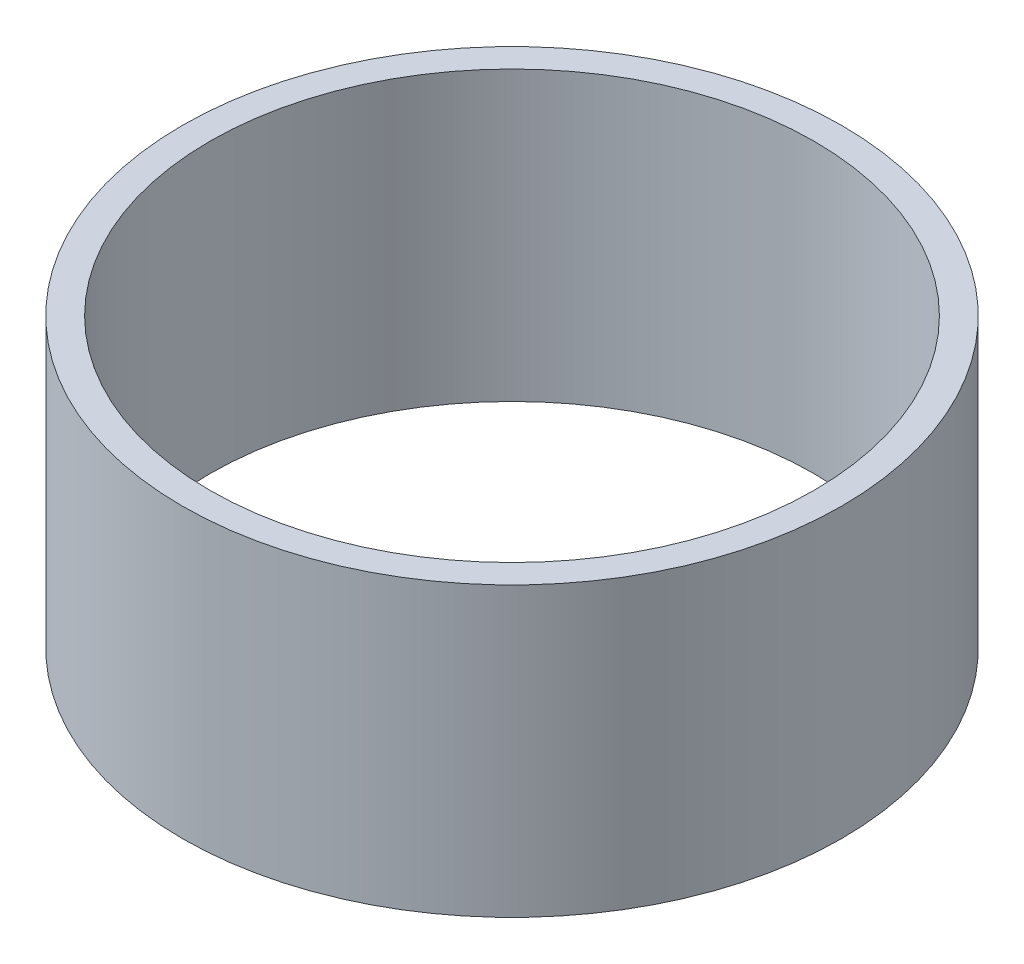
SolidWorks part; units mm, degrees
material "6061-T6 (SS)"
ref_plane "Front Plane" through (0, 0, 0) normal (0, 0, 1) x (1, 0, 0)
ref_plane "Top Plane" through (0, 0, 0) normal (0, 1, 0) x (1, 0, 0)
ref_plane "Right Plane" through (0, 0, 0) normal (1, 0, 0) x (0, 0, -1)
sketch "Sketch1" plane through (0, 0, 0) normal (0, 1, 0) x (1, 0, 0)
  circle A0 centre (0, 0) radius 76.2
  circle A1 centre (0, 0) radius 69.85
  dimension "D1" = 6.35
  dimension "D2" = 152.4
extrude "Boss-Extrude1" add sketch "Sketch1" along normal mid plane 66.548
